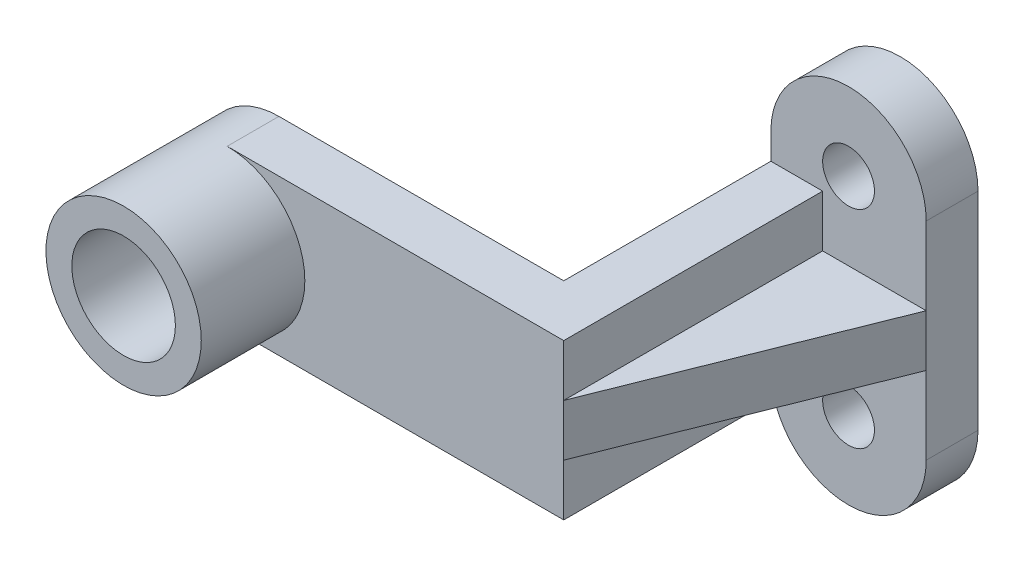
SolidWorks part; units mm, degrees
ref_plane "前基準面" through (0, 0, 0) normal (0, 0, 1) x (1, 0, 0)
ref_plane "上基準面" through (0, 0, 0) normal (0, 1, 0) x (1, 0, 0)
ref_plane "右基準面" through (0, 0, 0) normal (1, 0, 0) x (0, 0, -1)
sketch "草圖1" plane through (0, 0, 0) normal (0, 0, 1) x (1, 0, 0)
  line L0 (0, 20) -> (0, -20) construction
  line L1 (15, 20) -> (15, -20)
  line L2 (-15, 20) -> (-15, -20)
  arc A0 (15, 20) -> (-15, 20) centre (0, 20) ccw
  arc A1 (-15, -20) -> (15, -20) centre (0, -20) ccw
  circle A2 centre (0, -20) radius 5
  circle A3 centre (0, 20) radius 5
  point P3 (0, 0)
  dimension "D3" = 10
  dimension "D4" = 10
  dimension "D1" = 40
  dimension "D2" = 30
extrude "填料-伸長1" add sketch "草圖1" along normal blind 10
sketch "草圖2" plane through (0, 0, 10) normal (0, 0, 1) x (1, 0, 0)
  line L0 (15, -20) -> (15, 20) construction
  line L1 (15, 5) -> (-5, 5)
  line L2 (15, 5) -> (15, -5)
  line L3 (15, -5) -> (-5, -5)
  line L4 (-5, 5) -> (-5, -5)
  line L5 (-15, 20) -> (-15, -20) construction
  line L6 (-10.8831, 0) -> (24.3342, 0) construction
  dimension "D1" = 10
  dimension "D2" = 10
extrude "填料-伸長2" add sketch "草圖2" along normal blind 50
sketch "草圖4" plane through (0, -5, 0) normal (0, -1, 0) x (1, 0, 0)
  line L0 (-5, 60) -> (15, 10)
  line L1 (15, 10) -> (15, 60)
  line L2 (15, 60) -> (-5, 60)
extrude "除料-伸長1" cut sketch "草圖4" against normal blind 50
sketch "草圖5" plane through (0, 0, 10) normal (0, 0, 1) x (1, 0, 0)
  line L0 (-15, 20) -> (-15, -20) construction
  line L1 (-15, -15) -> (-5, -15)
  line L2 (-15, -15) -> (-15, 15)
  line L3 (-15, 15) -> (-5, 15)
  line L4 (-5, -15) -> (-5, 15)
  line L5 (0, 0) -> (-34.3073, 0) construction
  dimension "D1" = 10
  dimension "D2" = 30
extrude "填料-伸長3" add sketch "草圖5" along normal blind 50
sketch "草圖6" plane through (-15, 0, 0) normal (-1, 0, 0) x (0, 0, 1)
  line L0 (60, -15) -> (10, -15) construction
  line L1 (60, 15) -> (50, 15)
  line L2 (60, 15) -> (60, -15)
  line L3 (60, -15) -> (50, -15)
  line L4 (50, 15) -> (50, -15)
  dimension "D1" = 10
extrude "填料-伸長4" add sketch "草圖6" along normal blind 55
sketch "草圖7" plane through (0, 0, 60) normal (0, 0, 1) x (1, 0, 0)
  line L0 (-70, -15) -> (-70, 15) construction
  circle A0 centre (-70, 0) radius 10
  circle A1 centre (-70, 0) radius 15
  dimension "D1" = 20
  dimension "D2" = 5
extrude "填料-伸長5" add sketch "草圖7" along normal blind 20
sketch "草圖8" plane through (0, 0, 50) normal (0, 0, -1) x (-1, 0, 0)
  line L0 (70, 15) -> (70, -15) construction
  circle A0 centre (70, 0) radius 15
extrude "填料-伸長6" add sketch "草圖8" against normal blind 10
